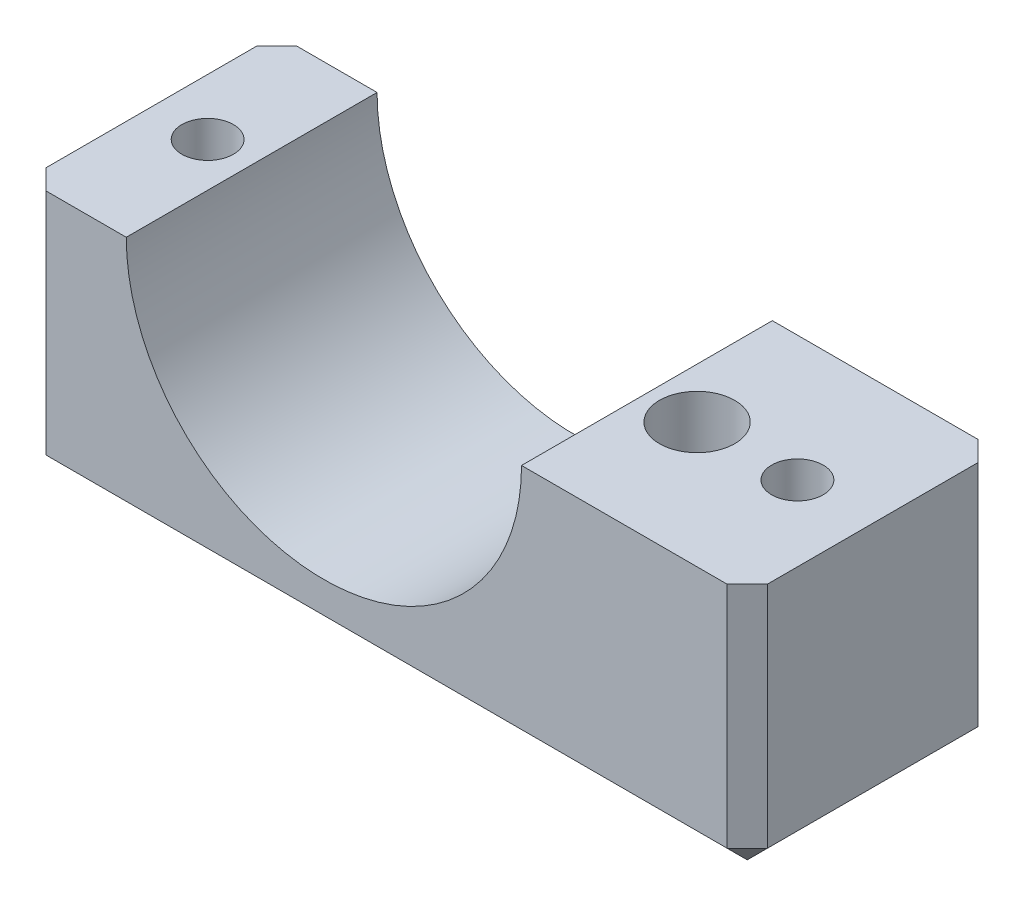
SolidWorks part; units mm, degrees
material "6061-T6 (SS)"
ref_plane "Front" through (0, 0, 0) normal (0, 0, 1) x (1, 0, 0)
ref_plane "Top" through (0, 0, 0) normal (0, 1, 0) x (1, 0, 0)
ref_plane "Right" through (0, 0, 0) normal (1, 0, 0) x (0, 0, -1)
sketch "Sketch1" plane through (0, 0, 0) normal (0, 0, 1) x (1, 0, 0)
  line L0 (0, 0) -> (12.7, 0)
  line L1 (50, 0) -> (-50, 0) construction
  line L2 (62.738, 0) -> (91.313, 0)
  line L3 (91.313, 0) -> (91.313, -31.496)
  line L4 (91.313, -31.496) -> (0, -31.496)
  line L5 (0, -50) -> (0, 50) construction
  line L6 (0, -31.496) -> (0, 0)
  arc A0 (12.7, 0) -> (62.738, 0) centre (37.719, 0) ccw
  dimension "D1" = 31.496
  dimension "D2" = 25.019
  dimension "D3" = 12.7
  dimension "D4" = 28.575
extrude "Boss-Extrude1" add sketch "Sketch1" along normal blind 31.75
sketch "Sketch2" plane through (0, -31.496, 0) normal (0, 1, 0) x (1, 0, 0)
  line L0 (12.7, -15.875) -> (7.1247, -15.875) construction
  line L1 (12.7, -31.75) -> (12.7, 0) construction
  line L2 (62.738, -15.875) -> (69.088, -15.875) construction
  line L3 (62.738, -31.75) -> (62.738, 0) construction
  line L4 (69.088, -15.875) -> (81.788, -15.875) construction
  line L5 (81.788, -15.875) -> (91.313, -15.875) construction
  line L6 (91.313, -31.75) -> (91.313, 0) construction
  line L7 (7.1247, -15.875) -> (7.1247, -25.4) construction
  line L8 (7.1247, -15.875) -> (7.1247, -6.35) construction
  line L9 (0, -31.75) -> (91.313, -31.75) construction
  dimension "D1" = 5.5753
  dimension "D2" = 6.35
  dimension "D3" = 12.7
  dimension "D4" = 6.35
hole_wizard "5/16-18 Tapped Hole1" positions "Sketch4" profile "Sketch3" tap size "5/16-18" standard "ANSI Inch" end condition through all
sketch "Sketch4" plane through (0, -31.496, 0) normal (0, -1, 0) x (-1, 0, 0)
  point P0 (-7.1247, -15.875)
  point P4 (-81.788, -15.875)
sketch "Sketch3" plane through (7.1247, -31.496, 15.875) normal (1, 0, 0) x (0, 0, -1)
  line L0 (0, 0) -> (0, 31.496)
  line L1 (0, 31.496) -> (3.2639, 31.496)
  line L2 (3.2639, 31.496) -> (3.2639, 0)
  line L5 (3.2639, 0) -> (0, 0)
  line L11 (0, -6.35) -> (0, 107.95) construction
  dimension "Thru Tap Drill Dia." = 6.5278
  dimension "Thru Tap Drill Depth" = 31.496
cosmetic thread "Hole Thread1" parameters "D2"=7.9375
cosmetic thread "Hole Thread2" parameters "D2"=7.9375
hole_wizard "3/8 (0.375) Clearance Dowel Hole2" positions "Sketch8" profile "Sketch7" hole size "3/8" standard "ANSI Inch" end condition through all
sketch "Sketch8" plane through (0, -31.496, 0) normal (0, -1, 0) x (-1, 0, 0)
  point P0 (-69.088, -15.875)
sketch "Sketch7" plane through (69.088, -31.496, 15.875) normal (1, 0, 0) x (0, 0, -1)
  line L0 (0, 0) -> (0, 31.496)
  line L1 (0, 31.496) -> (4.7625, 31.496)
  line L2 (4.7625, 31.496) -> (4.7625, 0)
  line L5 (4.7625, 0) -> (0, 0)
  line L11 (0, -6.35) -> (0, 107.95) construction
  dimension "Thru Hole Dia." = 9.525
  dimension "Thru Hole Depth" = 31.496
hole_wizard "1/4 (0.25) Clearance Dowel Hole1" positions "Sketch10" profile "Sketch9" hole size "1/4" standard "ANSI Inch"
sketch "Sketch10" plane through (0, -31.75, 0) normal (0, -1, 0) x (-1, 0, 0)
  point P0 (-7.1247, -25.4)
  point P3 (-7.1247, -6.35)
sketch "Sketch9" plane through (7.1247, -31.75, 25.4) normal (1, 0, 0) x (0, 0, -1)
  line L0 (0, 0) -> (0, 31.75)
  line L1 (0, 31.75) -> (3.175, 31.75)
  line L2 (3.175, 31.75) -> (3.175, 0)
  line L5 (3.175, 0) -> (0, 0)
  line L11 (0, -6.35) -> (0, 107.95) construction
  dimension "Thru Hole Dia." = 6.35
  dimension "Thru Hole Depth" = 31.75
sketch "Sketch11" plane through (0, 0, 0) normal (-1, 0, 0) x (0, 0, 1)
  line L0 (0, -31.496) -> (-25.4, -31.496) construction
  dimension "D1" = 25.4
chamfer "Chamfer1" distance 2.54 angle 45 8 edges at (91.313, -15.748, 31.75) (91.313, -15.748, 0) (0, -15.748, 31.75) (45.6565, -31.496, 31.75) (0, -15.748, 0) (45.6565, -31.496, 0) (91.313, -31.496, 15.875) (0, -31.496, 15.875)
